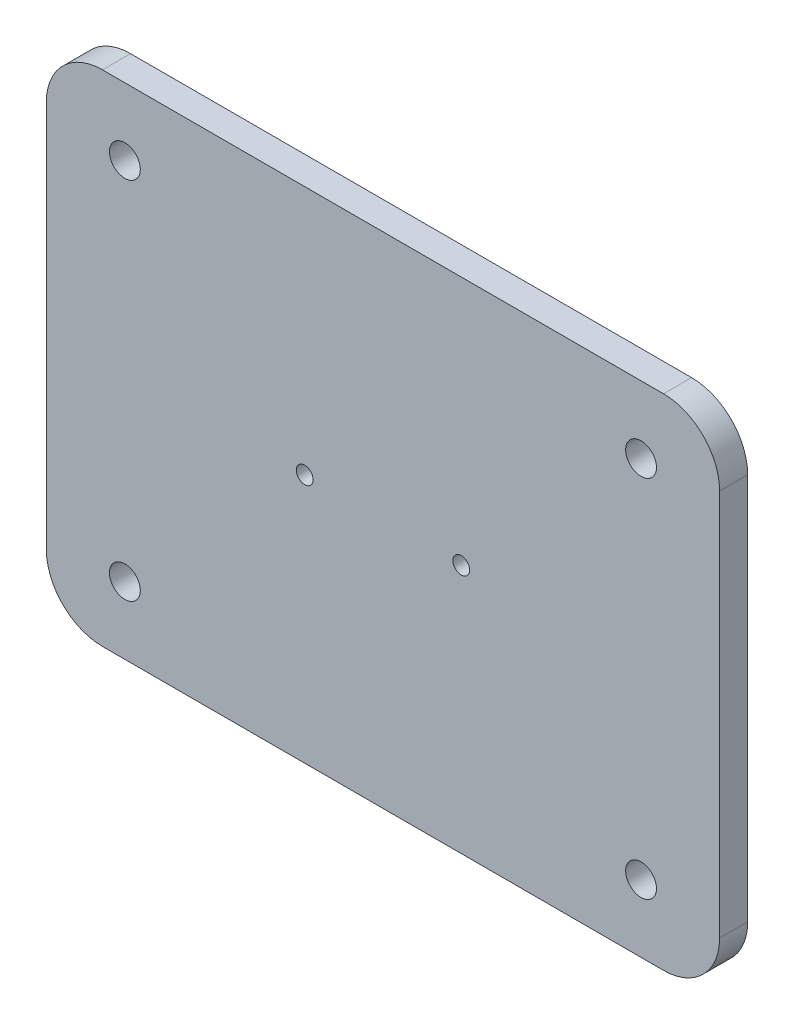
SolidWorks part; units mm, degrees
ref_plane "前视基准面" through (0, 0, 0) normal (0, 0, 1) x (1, 0, 0)
ref_plane "上视基准面" through (0, 0, 0) normal (0, 1, 0) x (1, 0, 0)
ref_plane "右视基准面" through (0, 0, 0) normal (1, 0, 0) x (0, 0, -1)
sketch "草图1" plane through (0, 0, 0) normal (0, 0, 1) x (1, 0, 0)
  line L1 (-83.4697, 38.6661) -> (66.5303, 38.6661)
  line L2 (-83.4697, 38.6661) -> (-83.4697, -50.3339)
  line L3 (-83.4697, -50.3339) -> (66.5303, -50.3339)
  line L4 (66.5303, 38.6661) -> (66.5303, -50.3339)
  dimension "D1" = 150
  dimension "D2" = 89
  dimension "D3" = 66.5303
  dimension "D4" = 38.6661
extrude "凸台-拉伸1" add sketch "草图1" along normal blind 5
ref_plane "基准面4" through (-83.4697, 38.6661, 5) normal (-1, 0, 0) x (0, 0, 1)
sketch "草图3" plane through (0, 0, 5) normal (0, 0, 1) x (1, 0, 0)
  line L0 (-76.2749, 38.6661) -> (-76.2749, 29.4161)
  line L1 (66.5303, 38.6661) -> (-83.4697, 38.6661) construction
  line L2 (-74.8911, -50.3339) -> (-74.8911, -41.0839)
  line L3 (-83.4697, -50.3339) -> (66.5303, -50.3339) construction
  line L4 (-83.4697, -50.3339) -> (-74.8911, -50.3339)
  line L5 (-83.4697, 38.6661) -> (-76.2749, 38.6661)
  line L6 (-83.4697, 38.6661) -> (36.5303, 38.6661)
  line L7 (36.5303, 38.6661) -> (36.5303, -50.3339)
  line L8 (36.5303, -50.3339) -> (-83.4697, -50.3339)
  line M6 (-83.4697, -50.3339) -> (66.5303, -50.3339)
  line M7 (66.5303, -50.3339) -> (66.5303, 38.6661)
  line M8 (66.5303, 38.6661) -> (-83.4697, 38.6661)
  dimension "D1" = 9.25
  dimension "D2" = 9.25
  dimension "D3" = 120
extrude "切除-拉伸1" cut sketch "草图3" against normal blind 5 contours L7 M8 M6 M7
sketch "草图4" plane through (0, 0, 5) normal (0, 0, 1) x (1, 0, 0)
  line L0 (-69.4697, 38.6661) -> (-69.4697, 26.6661)
  line L1 (36.5303, 38.6661) -> (-83.4697, 38.6661) construction
  line L2 (-69.4697, -50.3339) -> (-69.4697, -38.3339)
  line L3 (-83.4697, -50.3339) -> (36.5303, -50.3339) construction
  line L4 (-83.4697, 38.6661) -> (-69.4697, 38.6661)
  line L5 (-83.4697, 79.9161) -> (-83.4697, -2.5839) construction
  line L6 (-83.4697, -50.3339) -> (-69.4697, -50.3339)
  line L7 (-83.4697, 38.6661) -> (36.5303, -50.3339)
  line L8 (36.5303, 38.6661) -> (-83.4697, -50.3339)
  line L9 (-23.4697, -5.8339) -> (-23.4697, -50.3339)
  line L10 (-23.4697, -5.8339) -> (-23.4697, 38.6661)
  circle A0 centre (-69.4697, 26.6661) radius 2.75
  circle A1 centre (-69.4697, -38.3339) radius 2.75
  circle A2 centre (22.5303, 26.6661) radius 2.75
  circle A3 centre (22.5303, -38.3339) radius 2.75
  dimension "D1" = 12
  dimension "D2" = 12
  dimension "D3" = 14
  dimension "D4" = 14
extrude "切除-拉伸2" cut sketch "草图4" against normal blind 5
fillet "圆角2" radius 10 4 edges at (-83.4697, 38.6661, 2.5) (-83.4697, -50.3339, 2.5) (36.5303, -50.3339, 2.5) (36.5303, 38.6661, 2.5)
sketch "草图5" plane through (0, 0, 0) normal (0, 0, -1) x (-1, 0, 0)
  line L0 (-36.5303, -5.8339) -> (9.5197, -5.8339)
  line L3 (-36.5303, 28.6661) -> (-36.5303, -40.3339) construction
  line L4 (83.4697, -5.8339) -> (37.4197, -5.8339)
  line L5 (83.4697, 28.6661) -> (83.4697, -40.3339) construction
  circle A0 centre (9.5197, -5.8339) radius 1.5
  circle A1 centre (37.4197, -5.8339) radius 1.5
  dimension "D3" = 3
  dimension "D4" = 3
  dimension "D1" = 46.05
  dimension "D2" = 46.05
extrude "切除-拉伸7" cut sketch "草图5" against normal blind 10
sketch "草图7" plane through (0, 0, 5) normal (0, 0, 1) x (1, 0, 0)
  line L4 (26.5303, 38.6661) -> (-73.4697, 38.6661)
  line L5 (-83.4697, 28.6661) -> (-83.4697, -40.3339)
  line L6 (-73.4697, -50.3339) -> (26.5303, -50.3339)
  line L7 (36.5303, -40.3339) -> (36.5303, 28.6661)
  line L8 (26.5303, 38.6661) -> (-73.4697, 38.6661)
  line L9 (-83.4697, 28.6661) -> (-83.4697, -40.3339)
  line L10 (-73.4697, -50.3339) -> (26.5303, -50.3339)
  line L11 (36.5303, -40.3339) -> (36.5303, 28.6661)
  arc A4 (-73.4697, 38.6661) -> (-83.4697, 28.6661) centre (-73.4697, 28.6661) ccw
  arc A5 (-83.4697, -40.3339) -> (-73.4697, -50.3339) centre (-73.4697, -40.3339) ccw
  arc A6 (26.5303, -50.3339) -> (36.5303, -40.3339) centre (26.5303, -40.3339) ccw
  arc A7 (36.5303, 28.6661) -> (26.5303, 38.6661) centre (26.5303, 28.6661) ccw
  arc A8 (-73.4697, 38.6661) -> (-83.4697, 28.6661) centre (-73.4697, 28.6661) ccw
  arc A9 (-83.4697, -40.3339) -> (-73.4697, -50.3339) centre (-73.4697, -40.3339) ccw
  arc A10 (26.5303, -50.3339) -> (36.5303, -40.3339) centre (26.5303, -40.3339) ccw
  arc A11 (36.5303, 28.6661) -> (26.5303, 38.6661) centre (26.5303, 28.6661) ccw
  dimension "D1" = 0
